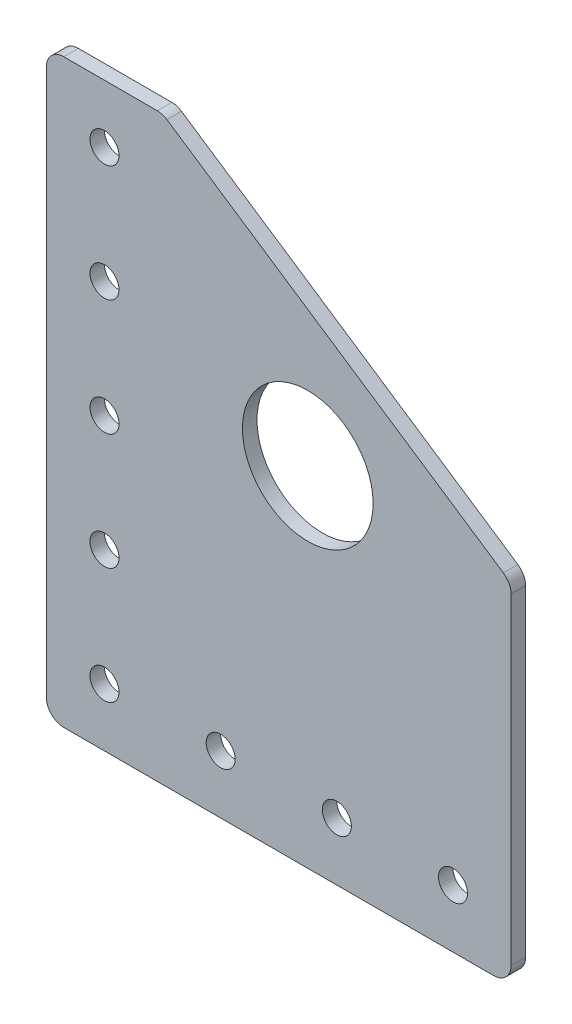
SolidWorks part; units mm, degrees
ref_plane "Front Plane" through (0, 0, 0) normal (0, 0, 1) x (1, 0, 0)
ref_plane "Top Plane" through (0, 0, 0) normal (0, 1, 0) x (1, 0, 0)
ref_plane "Right Plane" through (0, 0, 0) normal (1, 0, 0) x (0, 0, -1)
sketch "Sketch1" plane through (0, 0, 0) normal (0, 0, 1) x (1, 0, 0)
  line L0 (0, 0) -> (0, 127)
  line L1 (0, 127) -> (25.4, 127)
  line L2 (25.4, 127) -> (101.6, 76.2)
  line L3 (101.6, 76.2) -> (101.6, 0)
  line L4 (101.6, 0) -> (0, 0)
  line L5 (-907.4052, 12.7) -> (49092.5948, 12.7) construction
  line L6 (12.7, -873) -> (12.7, 49127) construction
  line L7 (-898.4, 76.2) -> (49101.6, 76.2) construction
  line L8 (12.7, 12.7) -> (38.1, 12.7) construction
  line L9 (12.7, 12.7) -> (12.7, 38.1) construction
  circle A0 centre (57.15, 76.2) radius 14.2875
  circle A1 centre (12.7, 12.7) radius 3.175
  circle A2 centre (38.1, 12.7) radius 3.175
  circle A3 centre (63.5, 12.7) radius 3.175
  circle A4 centre (88.9, 12.7) radius 3.175
  circle A5 centre (12.7, 38.1) radius 3.175
  circle A6 centre (12.7, 63.5) radius 3.175
  circle A7 centre (12.7, 88.9) radius 3.175
  circle A8 centre (12.7, 114.3) radius 3.175
  point P13 (12.7, 127)
  dimension "D5" = 28.575
  dimension "D8" = 6.35
  dimension "D1" = 127
  dimension "D2" = 25.4
  dimension "D3" = 101.6
  dimension "D4" = 76.2
  dimension "D6" = 44.45
  dimension "D7" = 12.7
  dimension "D10" = 25.4
  dimension "D12" = 25.4
  dimension "D9" = 4
  dimension "D11" = 5
extrude "Boss-Extrude1" add sketch "Sketch1" along normal blind 3.175
fillet "Fillet1" radius 3.81 5 edges at (0, 0, 1.5875) (101.6, 0, 1.5875) (101.6, 76.2, 1.5875) (25.4, 127, 1.5875) (0, 127, 1.5875)
